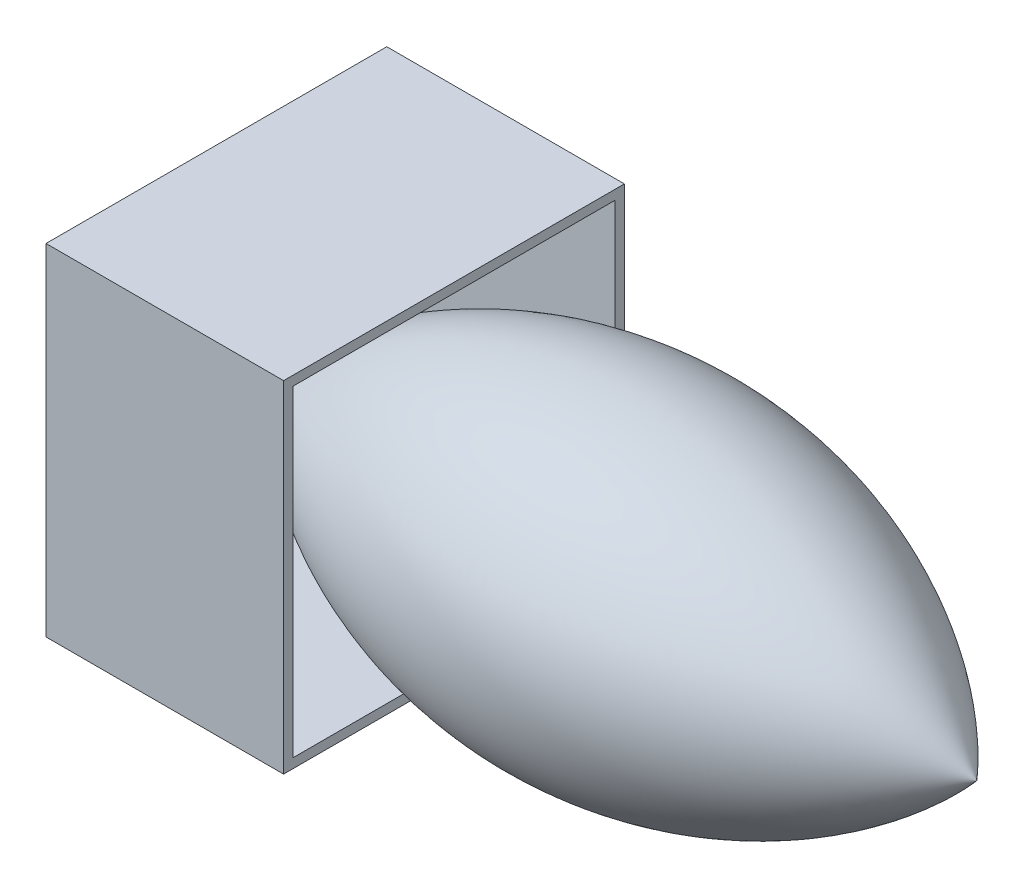
SolidWorks part; units mm, degrees
ref_plane "Front Plane" through (0, 0, 0) normal (0, 0, 1) x (1, 0, 0)
ref_plane "Top Plane" through (0, 0, 0) normal (0, 1, 0) x (1, 0, 0)
ref_plane "Right Plane" through (0, 0, 0) normal (1, 0, 0) x (0, 0, -1)
sketch "Sketch1" plane through (0, 0, 0) normal (0, 0, 1) x (1, 0, 0)
  line L0 (55, 0) -> (-55, 0) construction
  line L1 (0, 0) -> (4.3237, 0) construction
  line L2 (1.5, 0) -> (0, 0)
  arc A0 (1.5, 0) -> (0, 0) centre (0.75, -0.6614) ccw
  dimension "D1" = 1
  dimension "D2" = 1.5
revolve "Revolve1" add sketch "Sketch1" angle 360 about L1
sketch "Sketch2" plane through (0, 0, 0) normal (1, 0, 0) x (0, 0, -1)
  line L0 (-0.3586, 0.3586) -> (0.3586, 0.3586)
  line L1 (-0.3386, -0.3386) -> (0.3386, -0.3386)
  line L2 (-0.3386, -0.3386) -> (-0.3386, 0.3386)
  line L3 (-0.3386, 0.3386) -> (0.3386, 0.3386)
  line L4 (0.3386, -0.3386) -> (0.3386, 0.3386)
  line L5 (-0.3386, -0.3386) -> (0.3386, 0.3386) construction
  line L6 (-0.3386, 0.3386) -> (0.3386, -0.3386) construction
  line L7 (0.3586, -0.3586) -> (0.3586, 0.3586)
  line L8 (-0.3586, -0.3586) -> (0.3586, -0.3586)
  line L9 (-0.3586, -0.3586) -> (-0.3586, 0.3586)
  circle A0 centre (0, 0) radius 0.3386 construction
  point P0 (0, 0)
  dimension "D1" = 0.02
extrude "Boss-Extrude1" add sketch "Sketch2" along normal blind 0.4 and the other way blind 0.1
